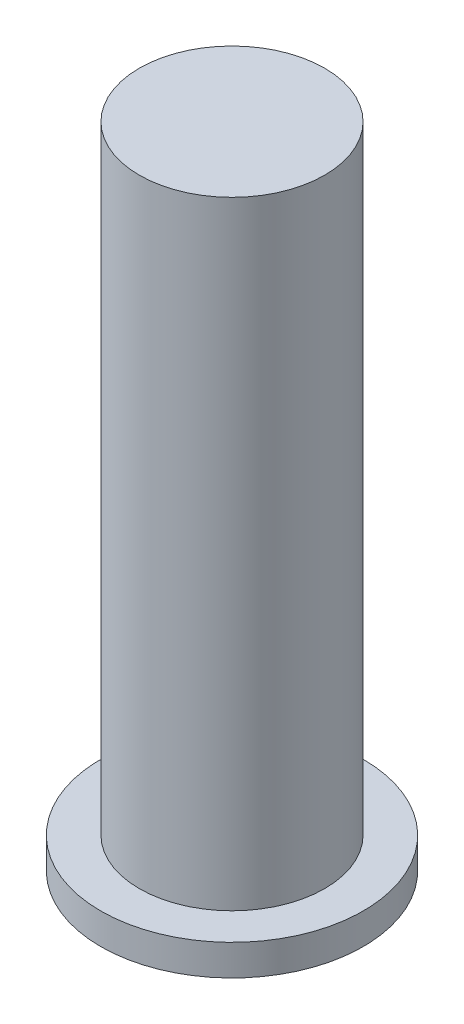
SolidWorks part; units mm, degrees
other "Suspension Pivot Shaft"
other "Suspension Pivot Shaft Left"
ref_plane "Front Plane" through (0, 0, 0) normal (0, 0, 1) x (1, 0, 0)
ref_plane "Top Plane" through (0, 0, 0) normal (0, 1, 0) x (1, 0, 0)
ref_plane "Right Plane" through (0, 0, 0) normal (1, 0, 0) x (0, 0, -1)
sketch3d "Main Profile Sketch datum points"
  point P0 (0, -123, 0)
  point P1 (10, -123, 0)
  point P2 (0, -123, 10)
ref_plane "Main Profile Sketch plane" through (0, -123, 0) normal (0, -1, 0) x (-1, 0, 0)
sketch "Main Profile Sketch" plane through (0, -123, 0) normal (0, -1, 0) x (-1, 0, 0)
  circle A0 centre (56.2917, 0) radius 8.5
extrude "Main Extrusion" add sketch "Main Profile Sketch" along normal blind 2 separate body
sketch3d "Detail Profile 2 Sketch datum points"
  point P0 (0, -125, 0)
  point P1 (10, -125, 0)
  point P2 (0, -125, 10)
ref_plane "Detail Profile 2 Sketch plane" through (0, -125, 0) normal (0, -1, 0) x (-1, 0, 0)
sketch "Detail Profile 2 Sketch" plane through (0, -125, 0) normal (0, -1, 0) x (-1, 0, 0)
  arc A0 (51.3844, -3.4524) -> (50.2917, 0) centre (56.2917, 0) ccw
  arc A1 (50.2917, 0) -> (51.3844, -3.4524) centre (56.2917, 0) ccw
extrude "Detail Extrusion 2" add sketch "Detail Profile 2 Sketch" along normal blind 31.5
sketch3d "Detail Profile 3 Sketch datum points"
  point P0 (0, -156.5, 0)
  point P1 (10, -156.5, 0)
  point P2 (0, -156.5, 10)
ref_plane "Detail Profile 3 Sketch plane" through (0, -156.5, 0) normal (0, -1, 0) x (-1, 0, 0)
sketch "Detail Profile 3 Sketch" plane through (0, -156.5, 0) normal (0, -1, 0) x (-1, 0, 0)
  arc A0 (51.3844, -3.4524) -> (50.2917, 0) centre (56.2917, 0) ccw
  arc A1 (50.2917, 0) -> (51.3844, -3.4524) centre (56.2917, 0) ccw
extrude "Detail Extrusion 3" add sketch "Detail Profile 3 Sketch" along normal blind 0.5
sketch3d "Detail Profile 4 Sketch datum points"
  point P0 (0, -157, 0)
  point P1 (10, -157, 0)
  point P2 (0, -157, 10)
ref_plane "Detail Profile 4 Sketch plane" through (0, -157, 0) normal (0, -1, 0) x (-1, 0, 0)
sketch "Detail Profile 4 Sketch" plane through (0, -157, 0) normal (0, -1, 0) x (-1, 0, 0)
  circle A0 centre (56.2917, 0) radius 6
extrude "Detail Extrusion 4" add sketch "Detail Profile 4 Sketch" along normal blind 8
sketch3d "Mirror1 profile datum points"
  point P0 (0, 0, 0)
  point P1 (10, 0, 0)
  point P2 (0, 0, 10)
ref_plane "Mirror1 profile plane" through (0, 0, 0) normal (0, -1, 0) x (-1, 0, 0)
mirror "Mirror1" about plane through (0, 0, 0) normal (0, -1, 0) of bodies 104
delete or keep bodies "Remove1" type delete bodies bodies 104
